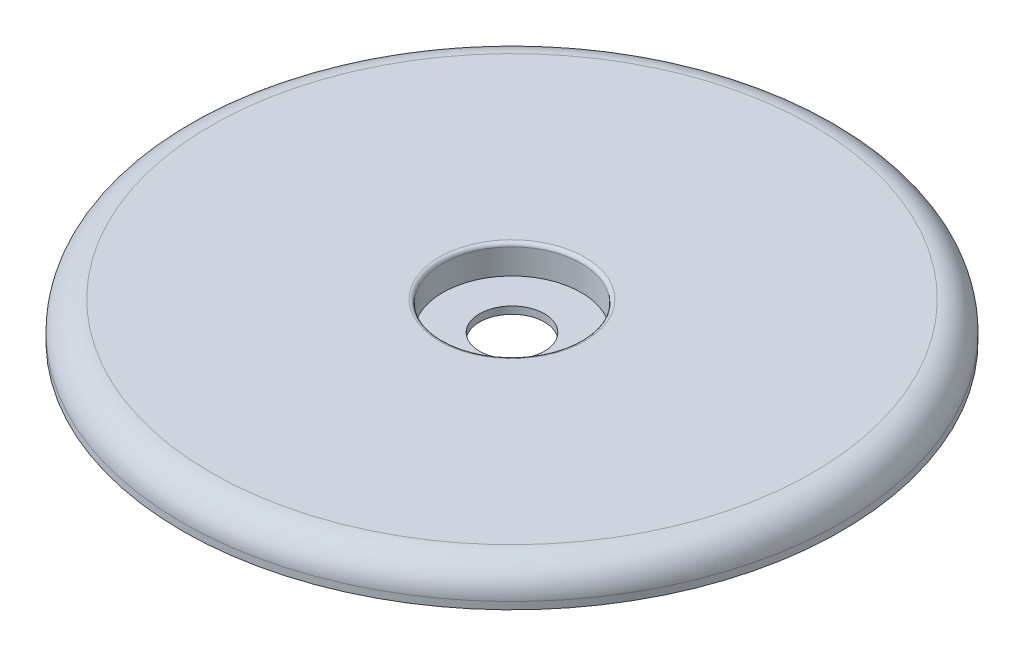
SolidWorks part; units mm, degrees
ref_plane "Front Plane" through (0, 0, 0) normal (0, 0, 1) x (1, 0, 0)
ref_plane "Top Plane" through (0, 0, 0) normal (0, 1, 0) x (1, 0, 0)
ref_plane "Right Plane" through (0, 0, 0) normal (1, 0, 0) x (0, 0, -1)
sketch "Sketch1" plane through (0, 0, 0) normal (0, 1, 0) x (1, 0, 0)
  circle A0 centre (0, 0) radius 45.72
extrude "Boss-Extrude1" add sketch "Sketch1" along normal blind 5
sketch "Sketch2" plane through (0, 5, 0) normal (0, 1, 0) x (1, 0, 0)
  circle A0 centre (0, 0) radius 9.6
  circle A1 centre (0, 0) radius 4.5
extrude "Cut-Extrude1" cut sketch "Sketch2" against normal blind 4 contours A0 A1 | A1
sketch "Sketch3" plane through (0, 1, 0) normal (0, 1, 0) x (1, 0, 0)
  circle A0 centre (0, 0) radius 4.5
extrude "Cut-Extrude2" cut sketch "Sketch3" against normal through all
fillet "Fillet1" radius 4 1 edges at (0, 5, 45.72)
fillet "Fillet2" radius 0.5 1 edges at (0, 5, 9.6)
